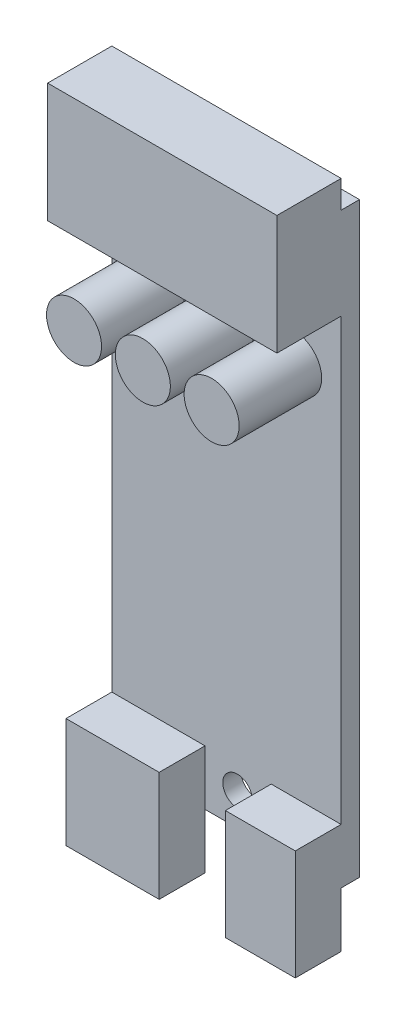
SolidWorks part; units mm, degrees
ref_plane "Front Plane" through (0, 0, 0) normal (0, 0, 1) x (1, 0, 0)
ref_plane "Top Plane" through (0, 0, 0) normal (0, 1, 0) x (1, 0, 0)
ref_plane "Right Plane" through (0, 0, 0) normal (1, 0, 0) x (0, 0, -1)
ref_plane "Plane1" through (0, 0, 0) normal (0, 0, -1) x (-1, 0, 0)
sketch "Sketch1" plane through (0, 0, 0) normal (0, 0, -1) x (-1, 0, 0)
  line L0 (0, 0) -> (0, 67)
  line L1 (0, 67) -> (-25, 67)
  line L2 (-25, 67) -> (-25, 0)
  line L3 (-25, 0) -> (0, 0)
extrude "Boss-Extrude1" add sketch "Sketch1" against normal blind 9
sketch "Sketch2" plane through (0, 0, 0) normal (-1, 0, 0) x (0, 0, 1)
  line L0 (0, 67) -> (0, 64)
  line L1 (0, 64) -> (2, 64)
  line L2 (2, 64) -> (2, 67)
  line L3 (2, 67) -> (0, 67)
extrude "Cut-Extrude1" cut sketch "Sketch2" against normal through all
sketch "Sketch3" plane through (0, 0, 0) normal (-1, 0, 0) x (0, 0, 1)
  line L0 (9, 54) -> (2, 54)
  line L1 (2, 54) -> (2, 0)
  line L2 (2, 0) -> (9, 0)
  line L3 (9, 0) -> (9, 54)
extrude "Cut-Extrude2" cut sketch "Sketch3" against normal through all
ref_plane "Plane2" through (0, 0, 0) normal (-1, 0, 0) x (0, -1, 0)
sketch "Sketch4" plane through (0, 0, 0) normal (-1, 0, 0) x (0, -1, 0)
  line L0 (-6, 2) -> (0, 2)
  line L1 (0, 2) -> (6, 2)
  line L2 (6, 2) -> (6, 7)
  line L3 (6, 7) -> (-6, 7)
  line L4 (-6, 7) -> (-6, 2)
extrude "Boss-Extrude2" add sketch "Sketch4" against normal blind 10.16
ref_plane "Plane3" through (25, 0, 0) normal (1, 0, 0) x (0, 0, -1)
sketch "Sketch5" plane through (25, 0, 0) normal (1, 0, 0) x (0, 0, -1)
  line L0 (-2, 0) -> (-2, 6)
  line L1 (-2, 6) -> (-7, 6)
  line L2 (-7, 6) -> (-7, -6)
  line L3 (-7, -6) -> (-2, -6)
  line L4 (-2, -6) -> (-2, 0)
extrude "Boss-Extrude3" add sketch "Sketch5" against normal blind 7.62
ref_plane "Plane4" through (0, 47.0647, 0) normal (0, -1, 0) x (1, 0, 0)
sketch "Sketch6" plane through (0, 47.0647, 0) normal (0, -1, 0) x (1, 0, 0)
  line L0 (22.8803, 11) -> (19.8803, 11)
  line L1 (19.8803, 11) -> (19.8803, 2)
  line L2 (19.8803, 2) -> (22.8803, 2)
  line L3 (22.8803, 2) -> (22.8803, 11)
  line L4 (19.8803, 11) -> (19.8803, 2) construction
revolve "Revolve1" add sketch "Sketch6" angle 360 about L4
sketch "Sketch7" plane through (0, 47.0647, 0) normal (0, -1, 0) x (1, 0, 0)
  line L0 (15.3803, 11) -> (12.3803, 11)
  line L1 (12.3803, 11) -> (12.3803, 2)
  line L2 (12.3803, 2) -> (15.3803, 2)
  line L3 (15.3803, 2) -> (15.3803, 11)
  line L4 (12.3803, 11) -> (12.3803, 2) construction
revolve "Revolve2" add sketch "Sketch7" angle 360 about L4
sketch "Sketch8" plane through (0, 47.0647, 0) normal (0, -1, 0) x (1, 0, 0)
  line L0 (7.8803, 11) -> (4.8803, 11)
  line L1 (4.8803, 11) -> (4.8803, 2)
  line L2 (4.8803, 2) -> (7.8803, 2)
  line L3 (7.8803, 2) -> (7.8803, 11)
  line L4 (4.8803, 11) -> (4.8803, 2) construction
revolve "Revolve3" add sketch "Sketch8" angle 360 about L4
hole_wizard "Ø3.2 (3.2) Diameter Hole1" positions "Sketch10" profile "Sketch9" hole size "Ø3.2" standard "ANSI Metric"
sketch "Sketch10" plane through (0, 0, 0) normal (0, 0, -1) x (-1, 0, 0)
  point P0 (-15.2, 40.7)
  point P1 (-13.7, 3.5)
sketch "Sketch9" plane through (15.2, 40.7, 0) normal (1, 0, 0) x (0, 1, 0)
  line L0 (0, 0) -> (0, 11)
  line L1 (0, 11) -> (1.6, 11)
  line L2 (1.6, 11) -> (1.6, 0)
  line L5 (1.6, 0) -> (0, 0)
  line L11 (0, -6.35) -> (0, 107.95) construction
  dimension "Thru Hole Dia." = 3.2
  dimension "Thru Hole Depth" = 11
